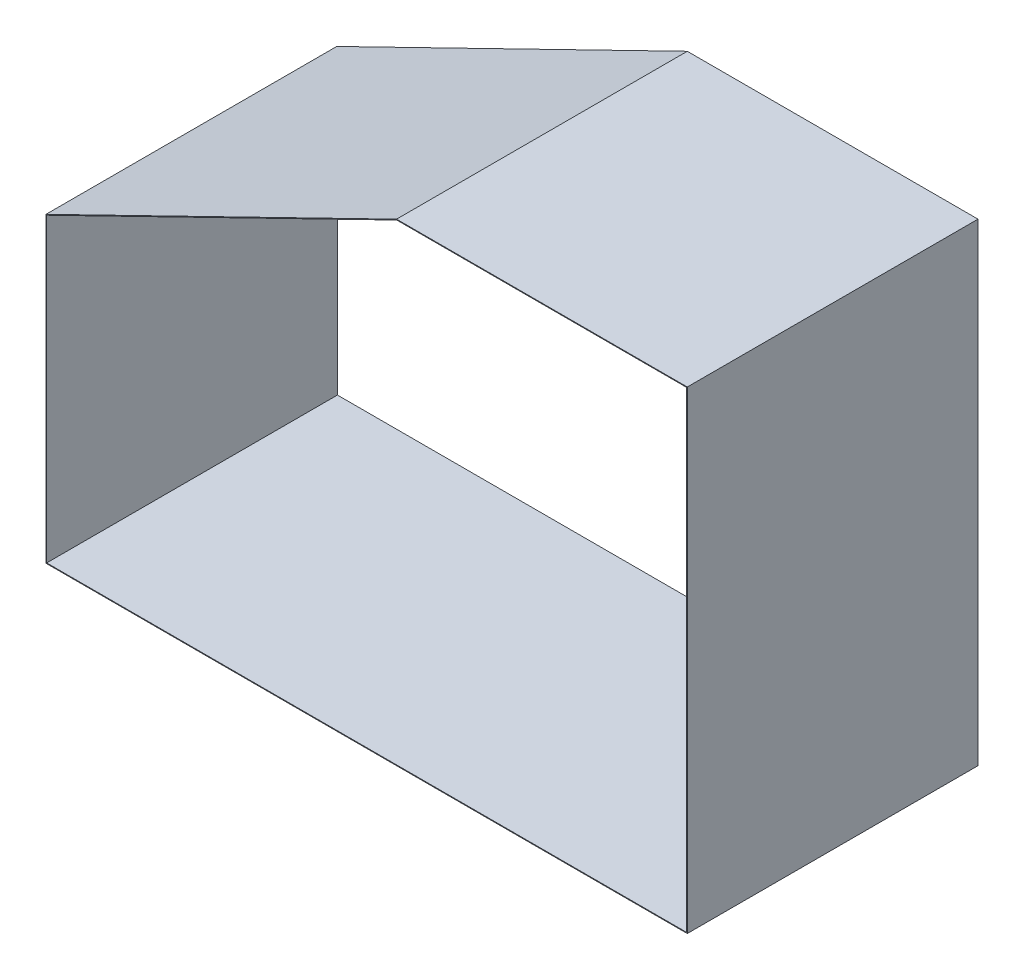
SolidWorks part; units mm, degrees
ref_plane "Front Plane" through (0, 0, 0) normal (0, 0, 1) x (1, 0, 0)
ref_plane "Top Plane" through (0, 0, 0) normal (0, 1, 0) x (1, 0, 0)
ref_plane "Right Plane" through (0, 0, 0) normal (1, 0, 0) x (0, 0, -1)
sketch "Sketch1" plane through (0, 0, 0) normal (0, 0, 1) x (1, 0, 0)
  line L0 (1221.8, 1649.71) -> (2235, 1649.71)
  line L1 (2235, 1649.71) -> (2235, 0)
  line L2 (2235, 0) -> (0, 0)
  line L3 (0, 0) -> (0, 1053.44)
  line L4 (0, 1053.44) -> (1221.8, 1649.71)
  line L5 (2.5, 1051.8782) -> (1222.3775, 1647.21)
  line L6 (1222.3775, 1647.21) -> (2232.5, 1647.21)
  line L7 (2232.5, 1647.21) -> (2232.5, 2.5)
  line L8 (2232.5, 2.5) -> (2.5, 2.5)
  line L9 (2.5, 2.5) -> (2.5, 1051.8782)
  point P4 (-1221.8, 1873.8332)
  point P7 (-1221.8, -700.2425)
  point P8 (-1221.8, 1161.8548)
  point P9 (-1221.8, -324.6934)
  point P10 (-1221.8, -1240.0942)
  point P11 (-1221.8, -575.0595)
  point P12 (-1221.8, -934.9606)
  point P13 (-1221.8, -934.9606)
  point P19 (0, 0)
  dimension "D1" = 1013.2
  dimension "D2" = 1649.71
  dimension "D3" = 2235
  dimension "D4" = 1053.44
  dimension "D5" = 2.5
extrude "Boss-Extrude1" add sketch "Sketch1" along normal blind 1013.2
